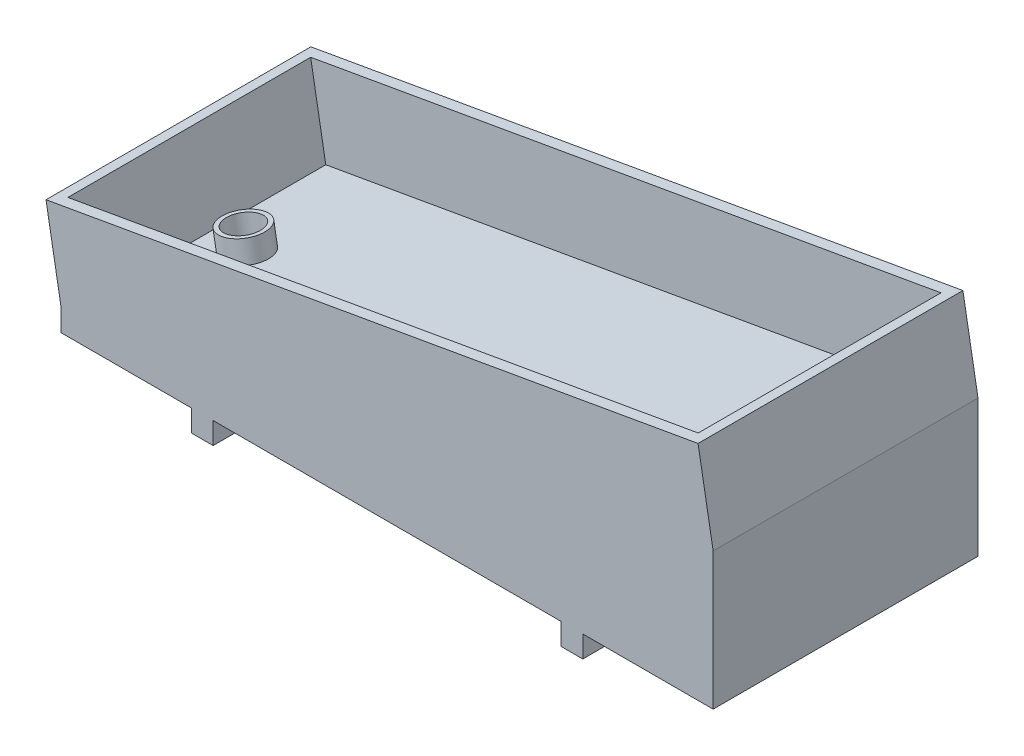
SolidWorks part; units mm, degrees
ref_plane "Front Plane" through (0, 0, 0) normal (0, 0, 1) x (1, 0, 0)
ref_plane "Top Plane" through (0, 0, 0) normal (0, 1, 0) x (1, 0, 0)
ref_plane "Right Plane" through (0, 0, 0) normal (1, 0, 0) x (0, 0, -1)
sketch "Sketch1" plane through (0, 0, 0) normal (0, 0, 1) x (1, 0, 0)
  line L0 (0, 0) -> (1500.847, 264.6398)
  line L1 (0, 0) -> (1500.847, 0)
  line L2 (1500.847, 0) -> (1500.847, 264.6398)
  line L3 (0, 0) -> (0, -50.8)
  line L4 (0, -50.8) -> (1500.847, -50.8)
  line L5 (1500.847, -50.8) -> (1500.847, 0)
extrude "Boss-Extrude2" add sketch "Sketch1" along normal blind 609.6 contours L1 L2 L0 | L4 L5 L1 L3
sketch "Sketch3" plane through (0, 0, 0) normal (-0.1736, 0.9848, 0) x (0.9848, 0.1736, 0)
  line L0 (0, 0) -> (0, -25.4)
  line L1 (0, -609.6) -> (0, 0) construction
  line L2 (0, -25.4) -> (1498.6, -25.4)
  line L3 (1498.6, -25.4) -> (1498.6, -584.2)
  line L4 (1498.6, -584.2) -> (25.4, -584.2)
  line L5 (25.4, -584.2) -> (25.4, -25.4)
extrude "Boss-Extrude4" add sketch "Sketch3" along normal blind 200
sketch "Sketch4" plane through (0, 0, 0) normal (-0.1736, 0.9848, 0) x (0.9848, 0.1736, 0)
  line L0 (25.4, -304.8) -> (125.4, -304.8)
  line L2 (25.4, -584.2) -> (25.4, -25.4) construction
  circle A0 centre (125.4, -304.8) radius 50
extrude "Boss-Extrude5" add sketch "Sketch4" along normal blind 50
sketch "Sketch5" plane through (-8.6824, 49.2404, 0) normal (-0.1736, 0.9848, 0) x (0.9848, 0.1736, 0)
  circle A0 centre (125.4, -304.8) radius 40
extrude "Cut-Extrude3" cut sketch "Sketch5" against normal blind 200
sketch "Sketch6" plane through (0, -50.8, 0) normal (0, -1, 0) x (-1, 0, 0)
  line L0 (-1500.847, -304.8) -> (-1200.847, -304.8)
  line L1 (-1500.847, -609.6) -> (-1500.847, 0) construction
  line L2 (-1200.847, -304.8) -> (-1200.847, -609.6)
  line L3 (0, -609.6) -> (-1500.847, -609.6) construction
  line L4 (-1200.847, -609.6) -> (-1150.847, -609.6)
  line L5 (-1150.847, -609.6) -> (-1150.847, 0)
  line L6 (0, 0) -> (-1500.847, 0) construction
  line L7 (-1150.847, 0) -> (-1200.847, 0)
  line L8 (-1200.847, 0) -> (-1200.847, -304.8)
  line L9 (0, -304.8) -> (-300, -304.8)
  line L10 (0, -609.6) -> (0, 0) construction
  line L11 (-300, -304.8) -> (-300, -609.6)
  line L12 (-300, -609.6) -> (-350, -609.6)
  line L13 (-350, -609.6) -> (-350, 0)
  line L14 (-350, 0) -> (-300, 0)
  line L15 (-300, 0) -> (-300, -304.8)
  line M3 (0, 0) -> (-1500.847, 0)
  line M5 (-1500.847, -609.6) -> (0, -609.6)
extrude "Boss-Extrude6" add sketch "Sketch6" along normal blind 50 contours L15 L13 L11 M3 M5 | L8 L2 L5 M3 M5
